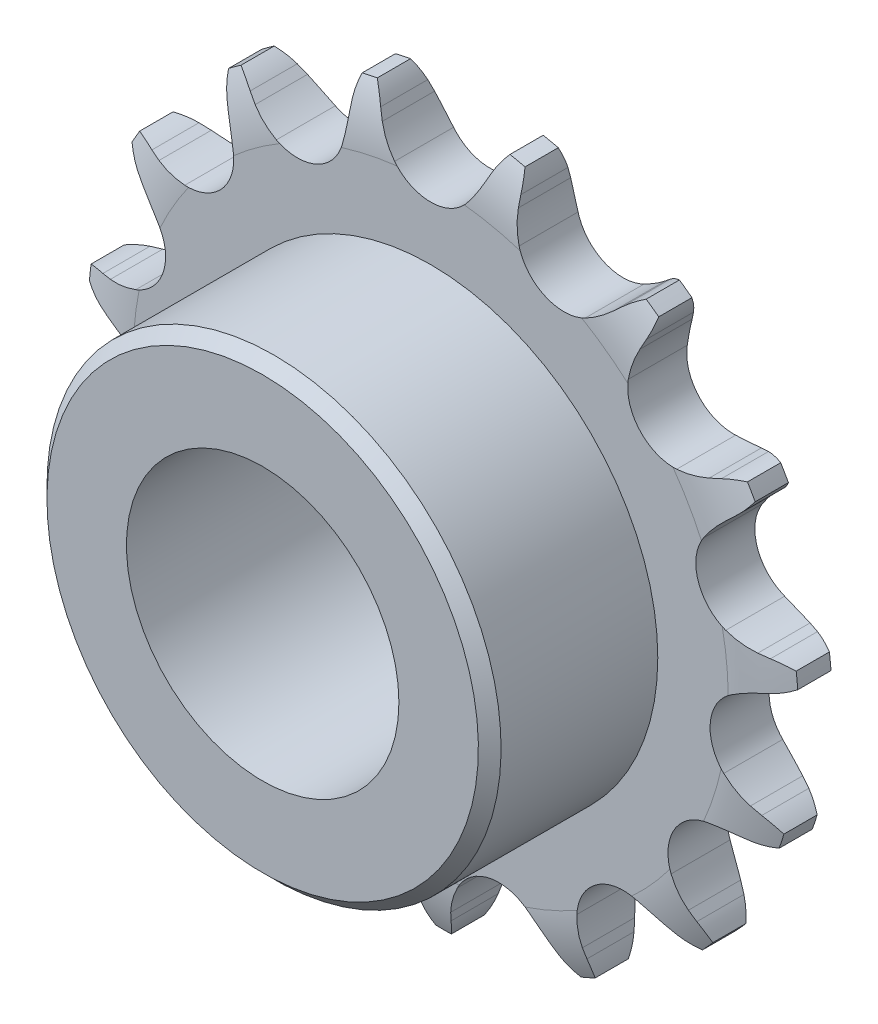
SolidWorks part; units mm, degrees
ref_plane "Front Plane" through (0, 0, 0) normal (0, 0, 1) x (1, 0, 0)
ref_plane "Top Plane" through (0, 0, 0) normal (0, 1, 0) x (1, 0, 0)
ref_plane "Right Plane" through (0, 0, 0) normal (1, 0, 0) x (0, 0, -1)
sketch "Sketch0" plane through (0, 0, 0) normal (0, 0, 1) x (1, 0, 0)
  line L0 (3, -14.1139) -> (0, 0) construction
  line L1 (0, 0) -> (8.4813, -11.6735) construction
  line L2 (0, 0) -> (-3, -14.1139) construction
  line L3 (3, -14.1139) -> (8.4813, -11.6735) construction
  line L4 (3, -14.1139) -> (-3, -14.1139) construction
  line L5 (5.4587, -13.8191) -> (5.1921, -13.4619)
  line L6 (3, -14.1139) -> (0, -14.7516) construction
  line L7 (0.6339, -14.8447) -> (0.7322, -14.4099)
  line L8 (0, -14.1139) -> (0, -15.9139) construction
  line L9 (4.2889, -12.5222) -> (0.9862, -16.6008) construction
  line L10 (0, 0) -> (0, -14.1139) construction
  line L11 (5.1921, -13.4619) -> (0.9862, -16.6008) construction
  line L12 (0, -15.9139) -> (0, -16.1712) construction
  line L13 (8.1159, -11.8362) -> (5.4587, -13.8191) construction
  circle A0 centre (0, 0) radius 15.9139 construction
  circle A1 centre (0, 0) radius 14.4292 construction
  arc A2 (-3.2007, -17.3745) -> (9.9908, -14.5706) centre (0, 0) ccw
  circle A3 centre (0, 0) radius 16.1712 construction
  circle A4 centre (3, -14.1139) radius 2 construction
  arc A7 (4.2889, -12.5222) -> (1.1751, -13.1841) centre (3, -14.1139) ccw
  circle A8 centre (3, -14.1139) radius 2.0481 construction
  arc A9 (5.4587, -13.8191) -> (9.9908, -14.5706) centre (8.1159, -11.8362) ccw
  arc A10 (5.1921, -13.4619) -> (4.2889, -12.5222) centre (0.9862, -16.6008) ccw
  arc A11 (0.6339, -14.8447) -> (-3.2007, -17.3745) centre (-2.6, -14.1139) cw
  arc A12 (0.7322, -14.4099) -> (1.1751, -13.1841) centre (5.8512, -15.5667) cw
  dimension "D1" = 2.0481
  dimension "R" = 2.0481
sketch "Sketch1" plane through (0, 0, 0) normal (1, 0, 0) x (0, 0, -1)
  line L0 (1.3, 0) -> (-1.3, 0)
  line L1 (-1.3, 0) -> (-1.3, 13.1014)
  line L2 (-1.3, 14.4292) -> (0, 14.4292) construction
  line L3 (-0.6, 15.9139) -> (0.6, 15.9139)
  line L5 (1.3, 13.1014) -> (1.3, 0)
  line L7 (0, 15.9139) -> (0, 0) construction
  line L8 (-1.3, 13.1014) -> (1.3, 13.1014) construction
  line L9 (0, 15.9139) -> (0, -15.9139) construction
  line L10 (-1.3, 13.1014) -> (-1.3, 15.9139) construction
  line L11 (-1.3, 15.9139) -> (-0.6, 15.9139) construction
  line L12 (0.6, 15.9139) -> (1.3, 15.9139) construction
  line L13 (1.3, 15.9139) -> (1.3, 13.1014) construction
  line L14 (0, 0) -> (-6.4008, 0) construction
  line L15 (-1.3, 14.4292) -> (-1.3, 10.3292) construction
  line L22 (1.3, 0) -> (-8.7, 0) construction
  line L24 (-1.3, 0) -> (-1.3, 10.3292) construction
  arc A0 (-0.6, 15.9139) -> (-1.3, 13.1014) centre (4.7, 13.1014) ccw
  arc A1 (0.6, 15.9139) -> (1.3, 13.1014) centre (-4.7, 13.1014) cw
  dimension "R" = 6
revolve "Revolve1" add sketch "Sketch1" angle 360 mid plane about L0
extrude "Cut-Extrude1" cut sketch "Sketch0" against normal through all and the other way through all
pattern_circular "CirPattern1" count 15 over 360 about axis through (0, 0, 0) along (0, 0, 1) of "Cut-Extrude1"
sketch "Sketch2" plane through (0, 0, 0) normal (0, 0, 1) x (1, 0, 0)
  circle A0 centre (0, 0) radius 3 construction
  circle A1 centre (0, 0) radius 10
  circle A2 centre (0, 0) radius 15.65 construction
  dimension "Bore" = 6
  dimension "Hub Dia." = 20
  dimension "OD" = 31.3
extrude "Boss-Extrude1" add sketch "Sketch2" along normal up to vertex (8.7 mm away) from surface at 1.3 starting at face at (0, 0, 1.3)
sketch "Sketch3" plane through (0, 0, 0) normal (0, 0, 1) x (1, 0, 0)
  circle A0 centre (0, 0) radius 3 construction
  circle A1 centre (0, 0) radius 3
extrude "Cut-Extrude2" cut sketch "Sketch3" along normal through all and the other way through all
sketch "Sketch4" plane through (0, 0, 0) normal (1, 0, 0) x (0, 0, -1)
  line L0 (-8.7, 10) -> (-8.7, 9.5)
  line L1 (-1.3, 15.9139) -> (-3.25, 15.9139)
  line L2 (-1.3, 15.9139) -> (-1.3, 10.3292)
  line L3 (-1.3, 10.3292) -> (-3.25, 10.3292)
  line L4 (-3.25, 15.9139) -> (-3.25, 10.3292)
  line L9 (-8.7, 9.5) -> (-8.2, 10)
  line L10 (-8.2, 10) -> (-8.7, 10)
  dimension "C" = 0.5
  dimension "D3" = 1.95
revolve "Cut-Revolve1" cut sketch "Sketch4" angle 360 mid plane about L22
sketch "Sketch5" plane through (0, 0, 0) normal (0, 0, 1) x (1, 0, 0)
  circle A0 centre (0, 0) radius 15.65 construction
  circle A1 centre (0, 0) radius 15.65
extrude "Cut-Extrude3" cut sketch "Sketch5" against normal through all and the other way through all flip side to cut
sketch "Sketch6" plane through (0, 0, 0) normal (0, 0, 1) x (1, 0, 0)
  circle A0 centre (0, 0) radius 6
  dimension "D1" = 12
extrude "Cut-Extrude4" cut sketch "Sketch6" along normal through all both and the other way through all
equation "\"360/N@Sketch0\" = 360/\"Teeth@CirPattern1\""
equation "\"Ds@Sketch0\" = 1.005 * \"Dr@Sketch0\" + ( 0.003 * 25.4 ) "
equation "\"R@Sketch0\" = 1/2 * \"Ds@Sketch0\""
equation "\"A@Sketch0\" = 35 +  ( 60 / \"Teeth@CirPattern1\" ) "
equation "\"B@Sketch0\" = 18 -  ( 56 / \"Teeth@CirPattern1\" )"
equation "\"ac@Sketch0\" = 0.8 * \"Dr@Sketch0\""
equation "\"ab@Sketch0\" = 1.4 * \"Dr@Sketch0\""
equation "\"J@Sketch0\" = 0.3 * \"Pitch@Sketch0\""
equation "\"D3@Sketch4\" = \"t@Sketch1\" * 3 / 4"
